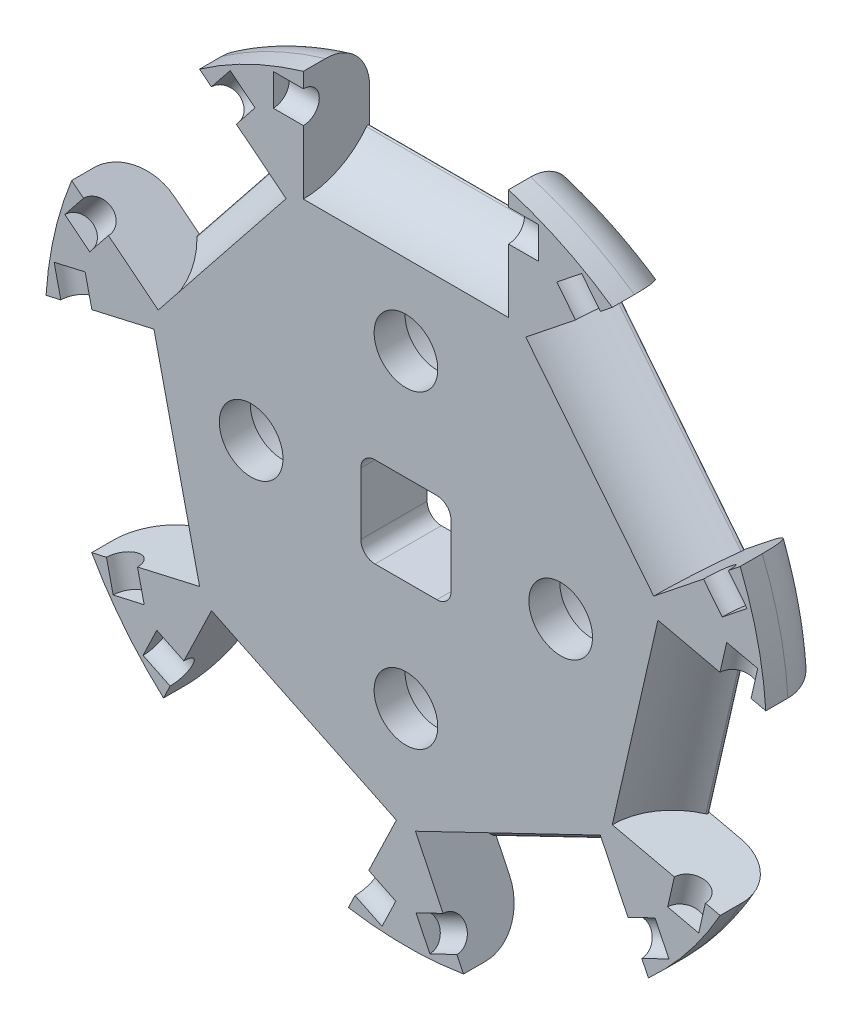
SolidWorks part; units mm, degrees
other "Markup1"
sketch "Sketch8" plane through (32.7336, 32.7336, 0) normal (0.5701, 0.1846, 0.8006) x (0.8043, 0.0736, -0.5897)
ref_plane "Front Plane" through (0, 0, 0) normal (0, 0, 1) x (1, 0, 0)
ref_plane "Top Plane" through (0, 0, 0) normal (0, 1, 0) x (1, 0, 0)
ref_plane "Right Plane" through (0, 0, 0) normal (1, 0, 0) x (0, 0, -1)
sketch "Sketch1" plane through (0, 0, 0) normal (0, 0, 1) x (1, 0, 0)
  circle A0 centre (0, 0) radius 25.8953
  dimension "D1" = 51.7906
extrude "Boss-Extrude2" add sketch "Sketch1" against normal blind 4.7625
fillet "Fillet1" radius 3.175 1 edges at (25.8953, 0, -4.7625)
sketch "Sketch2" plane through (0, 0, 0) normal (0, 0, 1) x (1, 0, 0)
  line L1 (-12.7, 25.8953) -> (12.7, 25.8953) construction
  line L2 (-7.366, 27.1653) -> (7.366, 27.1653)
  line L3 (-7.366, 27.1653) -> (-7.366, 16.7513)
  line L4 (-7.366, 16.7513) -> (7.366, 16.7513)
  line L5 (7.366, 27.1653) -> (7.366, 16.7513)
  line L6 (-7.366, 27.1653) -> (7.366, 16.7513) construction
  line L7 (-7.366, 16.7513) -> (7.366, 27.1653) construction
  line L35 (0, 0) -> (0, 25.8953) construction
  circle A1 centre (0, 0) radius 25.8953 construction
  point P10 (0, 21.9583)
  circle M7 centre (0, 0) radius 25.8953
  dimension "D1" = 14.732
  dimension "D2" = 10.414
  dimension "D3" = 1.27
  dimension "D4" = 25.4
extrude "Cut-Extrude2" cut sketch "Sketch2" against normal blind 12.7 contours L5 L3 L4 M7
pattern_circular "CirPattern1" count 7 over 360 about axis through (0, 0, 0) along (0, 0, 1) of "Cut-Extrude2"
ref_plane "Plane1" through (0, 0, 0) normal (1, 0, 0) x (0, 0, -1)
sketch "Sketch4" plane through (0, 0, 0) normal (1, 0, 0) x (0, 0, -1)
  line L0 (4.7625, 16.7513) -> (0, 16.7513) construction
  circle A0 centre (0, 22.5933) radius 1.143
  dimension "D1" = 2.286
  dimension "D2" = 5.842
extrude "Cut-Extrude4" cut sketch "Sketch4" against normal mid plane 19.05
pattern_circular "CirPattern2" count 7 over 360 about axis through (0, 0, 0) along (0, 0, 1) of "Cut-Extrude4"
sketch "Sketch5" plane through (0, 0, 0) normal (0, 0, 1) x (1, 0, 0)
  line L1 (-3.2385, -3.2385) -> (3.2385, -3.2385)
  line L2 (-3.2385, -3.2385) -> (-3.2385, 3.2385)
  line L3 (-3.2385, 3.2385) -> (3.2385, 3.2385)
  line L4 (3.2385, -3.2385) -> (3.2385, 3.2385)
  line L5 (-3.2385, -3.2385) -> (3.2385, 3.2385) construction
  line L6 (-3.2385, 3.2385) -> (3.2385, -3.2385) construction
  point P0 (0, 0)
  dimension "D1" = 6.477
extrude "Cut-Extrude5" cut sketch "Sketch5" against normal through all
sketch "Sketch6" plane through (0, 0, -4.7625) normal (0, 0, -1) x (-1, 0, 0)
  line L1 (55, 0) -> (-55, 0) construction
  line L2 (0, 55) -> (0, -55) construction
  circle A0 centre (0, 11.1125) radius 2.286
  circle A1 centre (11.1125, 0) radius 2.286
  circle A2 centre (0, -11.1125) radius 2.286
  circle A3 centre (-11.1125, 0) radius 2.286
  dimension "D4" = 4.572
  dimension "D1" = 11.1125
  dimension "D2" = 11.1125
extrude "Cut-Extrude7" cut sketch "Sketch6" against normal through all
sketch "Sketch7" plane through (0, 0, -4.7625) normal (0, 0, -1) x (-1, 0, 0)
  circle A0 centre (-11.1125, 0) radius 4.445
  circle A1 centre (11.1125, 0) radius 4.445
  circle A2 centre (0, -11.1125) radius 4.445
  circle A3 centre (0, 11.1125) radius 4.445
  dimension "D2" = 8.89
extrude "Cut-Extrude8" cut sketch "Sketch7" against normal blind 2.54
sketch "Sketch10" plane through (7.366, 0, 0) normal (-1, 0, 0) x (0, 0, 1)
  line L0 (-4.7625, 21.4931) -> (-4.7625, 16.7513) construction
  line L1 (-4.7625, 16.7513) -> (0, 16.7513)
  line L2 (-4.7625, 16.7513) -> (-4.7625, 19.4342)
  line L4 (0, 16.7513) -> (0, 16.8783)
  arc A0 (-4.7625, 19.4342) -> (0, 16.8783) centre (0, 22.5933) ccw
  dimension "D1" = 11.43
  dimension "D2" = 4.7625
extrude "Boss-Extrude4" add sketch "Sketch10" along normal up to next
fillet "Fillet2" radius 0.127 1 edges at (0, 19.4342, -4.7625)
pattern_circular "CirPattern5" count 7 over 360 of "Boss-Extrude4", "Fillet2"
fillet "Fillet3" radius 1.016 4 edges at (3.2385, -3.2385, -2.3813) (3.2385, 3.2385, -2.3813) (-3.2385, 3.2385, -2.3813) (-3.2385, -3.2385, -2.3813)
